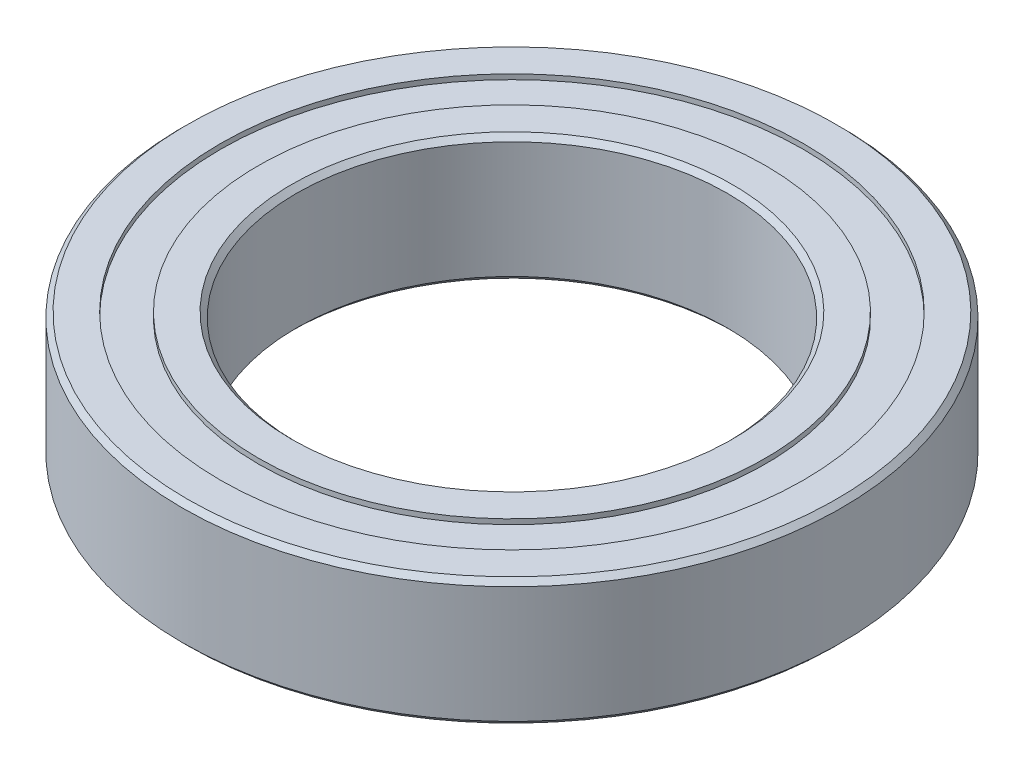
SolidWorks part; units mm, degrees
ref_plane "Front Plane" through (0, 0, 0) normal (0, 0, 1) x (1, 0, 0)
ref_plane "Top Plane" through (0, 0, 0) normal (0, 1, 0) x (1, 0, 0)
ref_plane "Right Plane" through (0, 0, 0) normal (1, 0, 0) x (0, 0, -1)
sketch "Sketch1" plane through (0, 0, 0) normal (0, 1, 0) x (1, 0, 0)
  circle A0 centre (0, 0) radius 13
  circle A1 centre (0, 0) radius 8.5
  dimension "D1" = 26
  dimension "D2" = 17
extrude "Boss-Extrude1" add sketch "Sketch1" along normal blind 5
sketch "Sketch2" plane through (0, 5, 0) normal (0, 1, 0) x (1, 0, 0)
  circle A4 centre (0, 0) radius 11.5
  circle A5 centre (0, 0) radius 11.5
  circle A7 centre (0, 0) radius 10
  circle A8 centre (0, 0) radius 10
  dimension "D1" = 1.5
  dimension "D2" = 1.5
extrude "Cut-Extrude1" cut sketch "Sketch2" against normal blind 0.2
sketch "Sketch3" plane through (0, 0, 0) normal (0, -1, 0) x (1, 0, 0)
  circle A1 centre (0, 0) radius 10 construction
  circle A4 centre (0, 0) radius 11.5 construction
  circle A7 centre (0, 0) radius 10
  circle A8 centre (0, 0) radius 11.5
extrude "Cut-Extrude2" cut sketch "Sketch3" against normal blind 0.2
chamfer "Chamfer1" distance 0.2 angle 45 4 edges at (0, 5, 13) (0, 0, 13) (0, 5, 8.5) (0, 0, 8.5)
